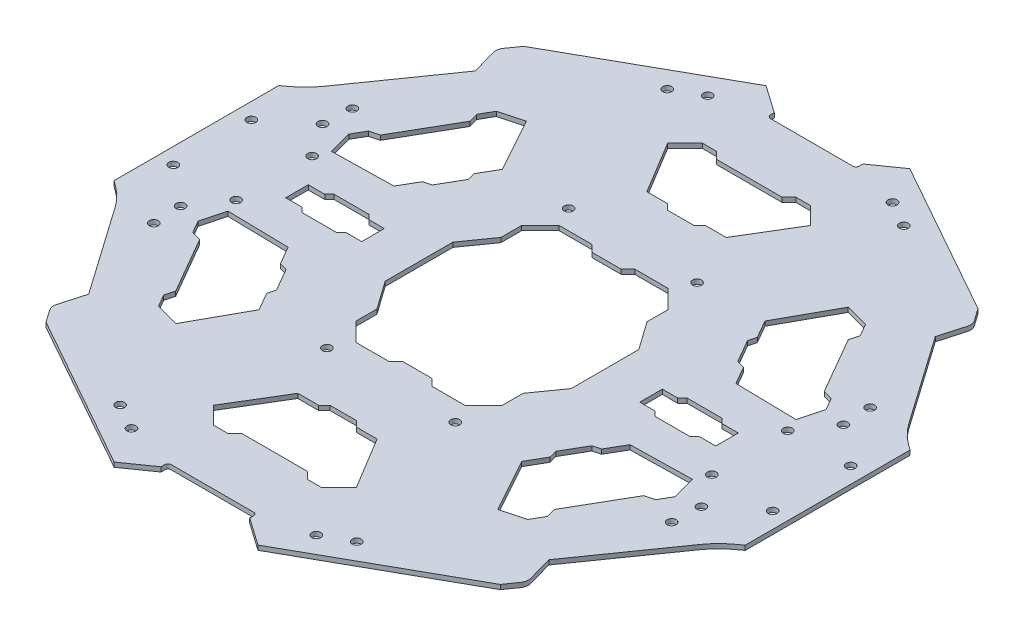
SolidWorks part; units mm, degrees
material "Thornel Mat VMA"
ref_plane "Front Plane" through (0, 0, 0) normal (0, 0, 1) x (1, 0, 0)
ref_plane "Top Plane" through (0, 0, 0) normal (0, 1, 0) x (1, 0, 0)
ref_plane "Right Plane" through (0, 0, 0) normal (1, 0, 0) x (0, 0, -1)
sketch "Sketch1" plane through (0, 0, 0) normal (0, 1, 0) x (1, 0, 0)
  line L0 (-35.3335, 90.1931) -> (213.3332, 90.1931) construction
  line L2 (-4.4405, 29.0018) -> (-6.5387, 31.1)
  line L3 (-6.5387, 31.1) -> (-16.6595, 31.1)
  line L4 (-16.6595, 31.1) -> (-22.3988, 25.3607)
  line L5 (-22.3988, 25.3607) -> (-22.3988, 19.0044)
  line L6 (-22.3988, 19.0044) -> (-28.5083, 10.3646)
  line L7 (-28.5083, 10.3646) -> (-28.5083, -10.3646)
  line L9 (-4.4405, 29.0018) -> (4.4405, 29.0018)
  line L11 (28.5083, 10.3646) -> (28.5083, -10.3646)
  line L12 (22.3988, 19.0044) -> (28.5083, 10.3646)
  line L13 (22.3988, 25.3607) -> (22.3988, 19.0044)
  line L14 (16.6595, 31.1) -> (22.3988, 25.3607)
  line L15 (6.5387, 31.1) -> (16.6595, 31.1)
  line L16 (4.4405, 29.0018) -> (6.5387, 31.1)
  line L17 (4.4405, -29.0018) -> (6.5387, -31.1)
  line L18 (6.5387, -31.1) -> (16.6595, -31.1)
  line L19 (16.6595, -31.1) -> (22.3988, -25.3607)
  line L20 (22.3988, -25.3607) -> (22.3988, -19.0044)
  line L21 (22.3988, -19.0044) -> (28.5083, -10.3646)
  line L22 (-4.4405, -29.0018) -> (4.4405, -29.0018)
  line L23 (-22.3988, -19.0044) -> (-28.5083, -10.3646)
  line L24 (-22.3988, -25.3607) -> (-22.3988, -19.0044)
  line L25 (-16.6595, -31.1) -> (-22.3988, -25.3607)
  line L26 (-6.5387, -31.1) -> (-16.6595, -31.1)
  line L27 (-4.4405, -29.0018) -> (-6.5387, -31.1)
sketch "Sketch2" plane through (0, 0, 0) normal (0, 1, 0) x (1, 0, 0)
  line L1 (12.5999, 91.8577) -> (-12.5999, 91.8577)
  line L2 (-13.5999, 92.8577) -> (-13.5999, 93.9984)
  line L3 (-13.5999, 93.9984) -> (-22.0367, 99.9168)
  line L4 (-22.0367, 99.9168) -> (-69.6356, 73.2211)
  line L5 (-69.6356, 73.2211) -> (-72.2643, 69.4739)
  line L6 (-72.6948, 66.9336) -> (-70.5171, 59.2436)
  line L7 (-70.5171, 59.2436) -> (-89.6548, 31.9621)
  line L8 (-94.9823, 26.5506) -> (-96.7634, 25.2591)
  line L9 (-96.7634, 25.2591) -> (-96.7634, -25.2591)
  line L13 (96.7634, 25.2591) -> (96.7634, -25.2591)
  line L14 (94.9823, 26.5506) -> (96.7634, 25.2591)
  line L15 (70.5171, 59.2436) -> (89.6548, 31.9621)
  line L16 (72.6948, 66.9336) -> (70.5171, 59.2436)
  line L17 (69.6356, 73.2211) -> (72.2643, 69.4739)
  line L18 (22.0367, 99.9168) -> (69.6356, 73.2211)
  line L19 (13.5999, 93.9984) -> (22.0367, 99.9168)
  line L20 (13.5999, 92.8577) -> (13.5999, 93.9984)
  line L21 (13.5999, -92.8577) -> (13.5999, -93.9984)
  line L22 (13.5999, -93.9984) -> (22.0367, -99.9168)
  line L23 (22.0367, -99.9168) -> (69.6356, -73.2211)
  line L24 (69.6356, -73.2211) -> (72.2643, -69.4739)
  line L25 (72.6948, -66.9336) -> (70.5171, -59.2436)
  line L26 (70.5171, -59.2436) -> (89.6548, -31.9621)
  line L27 (94.9823, -26.5506) -> (96.7634, -25.2591)
  line L28 (-94.9823, -26.5506) -> (-96.7634, -25.2591)
  line L29 (-70.5171, -59.2436) -> (-89.6548, -31.9621)
  line L30 (-72.6948, -66.9336) -> (-70.5171, -59.2436)
  line L31 (-69.6356, -73.2211) -> (-72.2643, -69.4739)
  line L32 (-22.0367, -99.9168) -> (-69.6356, -73.2211)
  line L33 (-13.5999, -93.9984) -> (-22.0367, -99.9168)
  line L34 (-13.5999, -92.8577) -> (-13.5999, -93.9984)
  line L35 (12.5999, -91.8577) -> (-12.5999, -91.8577)
  arc A0 (-12.5999, 91.8577) -> (-13.5999, 92.8577) centre (-12.5999, 92.8577) cw
  arc A1 (-72.2643, 69.4739) -> (-72.6948, 66.9336) centre (-69.8083, 67.751) ccw
  arc A2 (-89.6548, 31.9621) -> (-94.9823, 26.5506) centre (-108.484, 45.1706) cw
  arc A3 (89.6548, 31.9621) -> (94.9823, 26.5506) centre (108.484, 45.1706) ccw
  arc A4 (72.2643, 69.4739) -> (72.6948, 66.9336) centre (69.8083, 67.751) cw
  arc A5 (12.5999, 91.8577) -> (13.5999, 92.8577) centre (12.5999, 92.8577) ccw
  arc A6 (12.5999, -91.8577) -> (13.5999, -92.8577) centre (12.5999, -92.8577) cw
  arc A7 (72.2643, -69.4739) -> (72.6948, -66.9336) centre (69.8083, -67.751) ccw
  arc A8 (89.6548, -31.9621) -> (94.9823, -26.5506) centre (108.484, -45.1706) cw
  arc A9 (-89.6548, -31.9621) -> (-94.9823, -26.5506) centre (-108.484, -45.1706) ccw
  arc A10 (-72.2643, -69.4739) -> (-72.6948, -66.9336) centre (-69.8083, -67.751) cw
  arc A11 (-12.5999, -91.8577) -> (-13.5999, -92.8577) centre (-12.5999, -92.8577) ccw
  dimension "D1" = 1
  dimension "D2" = 3
  dimension "D3" = 23
sketch "Sketch3" plane through (0, 0, 0) normal (0, 1, 0) x (1, 0, 0)
  line L0 (5.7783, 53.5069) -> (4.0336, 51.7622)
  line L1 (-10.0263, 72.7746) -> (-12.1503, 74.8986)
  line L2 (-12.1503, 74.8986) -> (-16.55, 74.8986)
  line L3 (-16.55, 74.8986) -> (-21.86, 69.5886)
  line L4 (-21.86, 69.5886) -> (-12.1503, 53.5069)
  line L5 (-12.1503, 53.5069) -> (-5.7783, 53.5069)
  line L6 (-5.7783, 53.5069) -> (-4.0336, 51.7622)
  line L7 (-4.0336, 51.7622) -> (4.0336, 51.7622)
  line L10 (-10.0263, 72.7746) -> (10.0263, 72.7746)
  line L11 (12.1503, 53.5069) -> (5.7783, 53.5069)
  line L12 (21.86, 69.5886) -> (12.1503, 53.5069)
  line L13 (16.55, 74.8986) -> (21.86, 69.5886)
  line L14 (12.1503, 74.8986) -> (16.55, 74.8986)
  line L15 (10.0263, 72.7746) -> (12.1503, 74.8986)
  point P3 (0, 72.7746)
sketch "Sketch4" plane through (0, 0, 0) normal (0, 1, 0) x (1, 0, 0)
  circle A0 centre (-36.2675, 83.8589) radius 1.3745
sketch "Sketch5" plane through (0, 0, 0) normal (0, 1, 0) x (1, 0, 0)
  circle A0 centre (-28.3366, 88.3201) radius 1.3745
sketch "Sketch7" plane through (0, 0, 0) normal (0, 1, 0) x (1, 0, 0)
  circle A0 centre (-79.3711, 30.4329) radius 1.3745
sketch "Sketch8" plane through (0, 0, 0) normal (0, 1, 0) x (1, 0, 0)
  circle A0 centre (-79.8397, 21.7631) radius 1.3745
sketch "Sketch9" plane through (0, 0, 0) normal (0, 1, 0) x (1, 0, 0)
  circle A0 centre (-91.8575, 11.956) radius 1.3745
sketch "Sketch10" plane through (0, 0, 0) normal (0, 1, 0) x (1, 0, 0)
  circle A0 centre (-72.9171, 11.6447) radius 1.3745
sketch "Sketch11" plane through (0, 0, 0) normal (0, 1, 0) x (1, 0, 0)
  circle A0 centre (-19.6829, 37.0577) radius 1.3745
sketch "Sketch12" plane through (0, 0, 0) normal (0, 1, 0) x (1, 0, 0)
  line L0 (-42.6182, -3.4602) -> (-42.6182, 3.4602)
  line L1 (-42.6182, 3.4602) -> (-47.3427, 3.4602)
  line L2 (-47.3427, 3.4602) -> (-48.771, 4.8885)
  line L3 (-48.771, 4.8885) -> (-59.4286, 4.8885)
  line L4 (-59.4286, 4.8885) -> (-60.8569, 3.4602)
  line L5 (-60.8569, 3.4602) -> (-65.911, 3.4602)
  line L6 (-65.911, 3.4602) -> (-65.911, -3.4602)
  line L8 (-60.8569, -3.4602) -> (-65.911, -3.4602)
  line L9 (-59.4286, -4.8885) -> (-60.8569, -3.4602)
  line L10 (-48.771, -4.8885) -> (-59.4286, -4.8885)
  line L11 (-47.3427, -3.4602) -> (-48.771, -4.8885)
  line L12 (-42.6182, -3.4602) -> (-47.3427, -3.4602)
  point P12 (-65.911, 0)
  point P17 (-42.6182, 0)
ref_plane "Plane2" through (0, 1.4, 0) normal (0, 1, 0) x (1, 0, 0)
sketch "Sketch13" plane through (0, 1.4, 0) normal (0, 1, 0) x (1, 0, 0)
  line L1 (12.5999, 91.8577) -> (-12.5999, 91.8577)
  line L2 (-13.5999, 92.8577) -> (-13.5999, 93.9984)
  line L3 (-13.5999, 93.9984) -> (-22.0367, 99.9168)
  line L4 (-22.0367, 99.9168) -> (-69.6356, 73.2211)
  line L5 (-69.6356, 73.2211) -> (-72.2643, 69.4739)
  line L6 (-72.6948, 66.9336) -> (-70.5171, 59.2436)
  line L7 (-70.5171, 59.2436) -> (-89.6548, 31.9621)
  line L8 (-94.9823, 26.5506) -> (-96.7634, 25.2591)
  line L9 (-96.7634, 25.2591) -> (-96.7634, -25.2591)
  line L13 (96.7634, 25.2591) -> (96.7634, -25.2591)
  line L14 (94.9823, 26.5506) -> (96.7634, 25.2591)
  line L15 (70.5171, 59.2436) -> (89.6548, 31.9621)
  line L16 (72.6948, 66.9336) -> (70.5171, 59.2436)
  line L17 (69.6356, 73.2211) -> (72.2643, 69.4739)
  line L18 (22.0367, 99.9168) -> (69.6356, 73.2211)
  line L19 (13.5999, 93.9984) -> (22.0367, 99.9168)
  line L20 (13.5999, 92.8577) -> (13.5999, 93.9984)
  line L21 (13.5999, -92.8577) -> (13.5999, -93.9984)
  line L22 (13.5999, -93.9984) -> (22.0367, -99.9168)
  line L23 (22.0367, -99.9168) -> (69.6356, -73.2211)
  line L24 (69.6356, -73.2211) -> (72.2643, -69.4739)
  line L25 (72.6948, -66.9336) -> (70.5171, -59.2436)
  line L26 (70.5171, -59.2436) -> (89.6548, -31.9621)
  line L27 (94.9823, -26.5506) -> (96.7634, -25.2591)
  line L28 (-94.9823, -26.5506) -> (-96.7634, -25.2591)
  line L29 (-70.5171, -59.2436) -> (-89.6548, -31.9621)
  line L30 (-72.6948, -66.9336) -> (-70.5171, -59.2436)
  line L31 (-69.6356, -73.2211) -> (-72.2643, -69.4739)
  line L32 (-22.0367, -99.9168) -> (-69.6356, -73.2211)
  line L33 (-13.5999, -93.9984) -> (-22.0367, -99.9168)
  line L34 (-13.5999, -92.8577) -> (-13.5999, -93.9984)
  line L35 (12.5999, -91.8577) -> (-12.5999, -91.8577)
  arc A0 (-12.5999, 91.8577) -> (-13.5999, 92.8577) centre (-12.5999, 92.8577) cw
  arc A1 (-72.2643, 69.4739) -> (-72.6948, 66.9336) centre (-69.8083, 67.751) ccw
  arc A2 (-89.6548, 31.9621) -> (-94.9823, 26.5506) centre (-108.484, 45.1706) cw
  arc A3 (89.6548, 31.9621) -> (94.9823, 26.5506) centre (108.484, 45.1706) ccw
  arc A4 (72.2643, 69.4739) -> (72.6948, 66.9336) centre (69.8083, 67.751) cw
  arc A5 (12.5999, 91.8577) -> (13.5999, 92.8577) centre (12.5999, 92.8577) ccw
  arc A6 (12.5999, -91.8577) -> (13.5999, -92.8577) centre (12.5999, -92.8577) cw
  arc A7 (72.2643, -69.4739) -> (72.6948, -66.9336) centre (69.8083, -67.751) ccw
  arc A8 (89.6548, -31.9621) -> (94.9823, -26.5506) centre (108.484, -45.1706) cw
  arc A9 (-89.6548, -31.9621) -> (-94.9823, -26.5506) centre (-108.484, -45.1706) ccw
  arc A10 (-72.2643, -69.4739) -> (-72.6948, -66.9336) centre (-69.8083, -67.751) cw
  arc A11 (-12.5999, -91.8577) -> (-13.5999, -92.8577) centre (-12.5999, -92.8577) ccw
  dimension "D1" = 1
  dimension "D2" = 3
  dimension "D3" = 23
loft "Loft1" add profiles "Sketch13", "Sketch2"
extrude "Cut-Extrude1" cut sketch "Sketch3" against normal through all both and the other way through all
sketch "Sketch15" plane through (0, 0, 0) normal (0, 0, 1) x (1, 0, 0)
  line L0 (0, 0) -> (0, 110.3314)
pattern_circular "CirPattern1" count 6 over 360 about axis through (0, 0, 0) along (0, 1, 0) of "Cut-Extrude1"
extrude "Cut-Extrude2" cut sketch "Sketch1" against normal through all both and the other way through all
extrude "Cut-Extrude3" cut sketch "Sketch5" against normal through all both and the other way through all
extrude "Cut-Extrude4" cut sketch "Sketch4" against normal through all both and the other way through all
extrude "Cut-Extrude5" cut sketch "Sketch7" against normal through all both and the other way through all
extrude "Cut-Extrude6" cut sketch "Sketch8" against normal through all both and the other way through all
extrude "Cut-Extrude7" cut sketch "Sketch9" against normal through all both and the other way through all
extrude "Cut-Extrude8" cut sketch "Sketch10" against normal through all both and the other way through all
extrude "Cut-Extrude9" cut sketch "Sketch12" against normal through all both and the other way through all
extrude "Cut-Extrude10" cut sketch "Sketch11" against normal through all both and the other way through all
mirror "Mirror1" about plane through (0, 0, 0) normal (1, 0, 0) of "Cut-Extrude9"
mirror "Mirror2" about plane through (0, 0, 0) normal (1, 0, 0) of "Cut-Extrude10", "Cut-Extrude8", "Cut-Extrude7", "Cut-Extrude6", "Cut-Extrude5", "Cut-Extrude4", "Cut-Extrude3"
mirror "Mirror3" about plane through (0, 0, 0) normal (0, 0, 1) of "Cut-Extrude10", "Cut-Extrude8", "Cut-Extrude7", "Cut-Extrude6", "Cut-Extrude5", "Cut-Extrude4", "Mirror2", "Cut-Extrude3"
